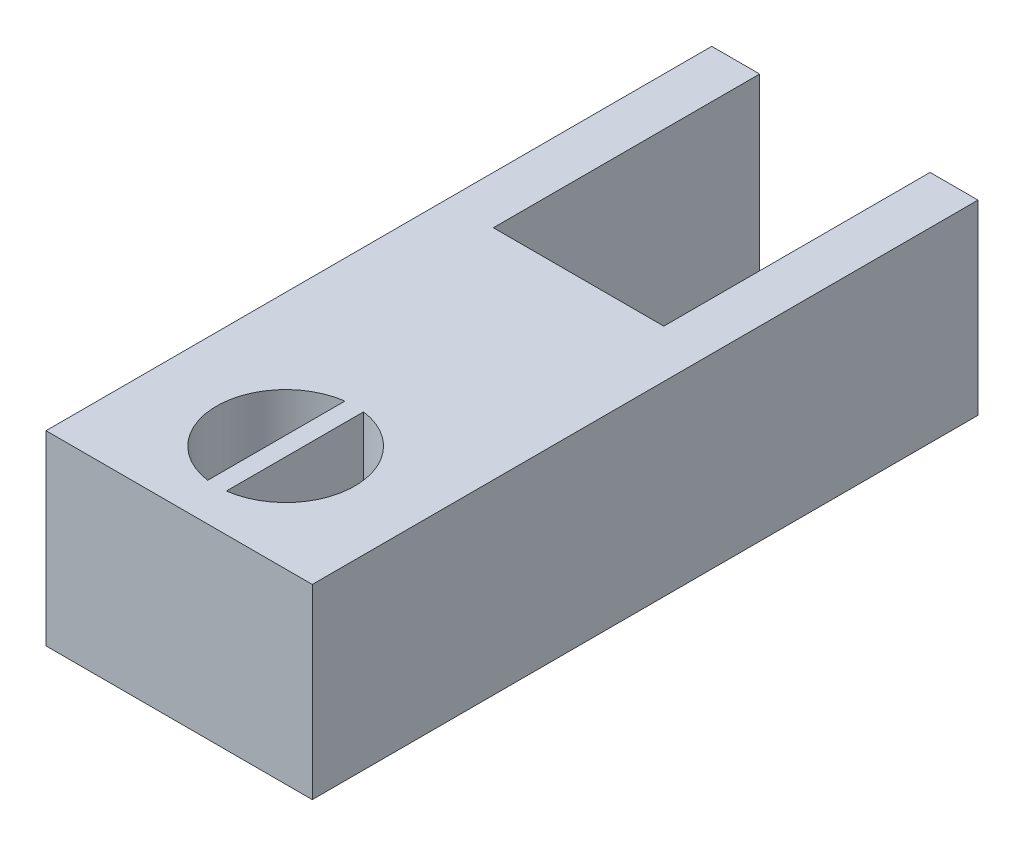
SolidWorks part; units mm, degrees
ref_plane "Front Plane" through (0, 0, 0) normal (0, 0, 1) x (1, 0, 0)
ref_plane "Top Plane" through (0, 0, 0) normal (0, 1, 0) x (1, 0, 0)
ref_plane "Right Plane" through (0, 0, 0) normal (1, 0, 0) x (0, 0, -1)
sketch "Sketch1" plane through (0, 0, 0) normal (0, 1, 0) x (1, 0, 0)
  line L1 (0, 0) -> (12.7, 0)
  line L2 (0, 0) -> (0, 31.75)
  line L3 (0, 31.75) -> (12.7, 31.75)
  line L4 (12.7, 0) -> (12.7, 31.75)
  dimension "D1" = 12.7
  dimension "D2" = 31.75
extrude "Boss-Extrude1" add sketch "Sketch1" along normal blind 8.89
sketch "Sketch2" plane through (0, 8.89, 0) normal (0, 1, 0) x (1, 0, 0)
  line L0 (12.7, 31.75) -> (0, 31.75) construction
  line L1 (2.286, 31.75) -> (10.414, 31.75)
  line L2 (2.286, 31.75) -> (2.286, 19.05)
  line L3 (2.286, 19.05) -> (10.414, 19.05)
  line L4 (10.414, 31.75) -> (10.414, 19.05)
  line L5 (0, 31.75) -> (0, 0) construction
  line L6 (12.7, 0) -> (12.7, 31.75) construction
  line L7 (0, 0) -> (12.7, 0) construction
  line L8 (6.35, 5.08) -> (6.35, 14.3202) construction
  line L9 (5.9055, 8.872) -> (6.7945, 8.872)
  line L10 (5.9055, 8.872) -> (5.9055, 1.0957)
  line L11 (5.9055, 1.0957) -> (6.7945, 1.0957)
  line L12 (6.7945, 8.872) -> (6.7945, 1.0957)
  circle A0 centre (6.35, 5.08) radius 3.302
  line M13 (12.7, 31.75) -> (0, 31.75)
  dimension "D3" = 6.604
  dimension "D1" = 8.128
  dimension "D2" = 2.286
  dimension "D4" = 6.35
  dimension "D5" = 5.08
  dimension "D6" = 12.7
  dimension "D7" = 0.889
  dimension "D8" = 0.4445
extrude "Cut-Extrude1" cut sketch "Sketch2" against normal blind 8.89 contours L4 L2 L3 M13 | L12 A0 | L10 A0
